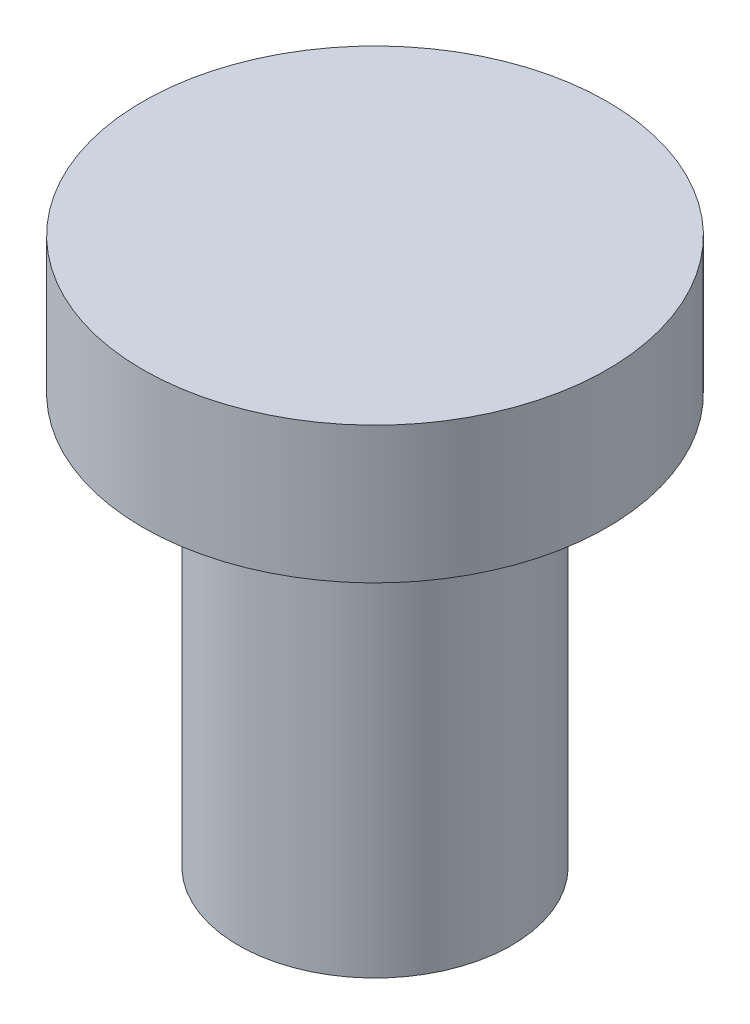
SolidWorks part; units mm, degrees
ref_plane "정면" through (0, 0, 0) normal (0, 0, 1) x (1, 0, 0)
ref_plane "윗면" through (0, 0, 0) normal (0, 1, 0) x (1, 0, 0)
ref_plane "우측면" through (0, 0, 0) normal (1, 0, 0) x (0, 0, -1)
sketch "스케치1" plane through (0, 0, 0) normal (0, 1, 0) x (1, 0, 0)
  circle A0 centre (0, 0) radius 1.7
  dimension "D1" = 3.4
extrude "보스-돌출1" add sketch "스케치1" along normal blind 1
sketch "스케치2" plane through (0, 0, 0) normal (0, -1, 0) x (1, 0, 0)
  circle A0 centre (0, 0) radius 1
  dimension "D1" = 2
extrude "보스-돌출2" add sketch "스케치2" along normal blind 3
